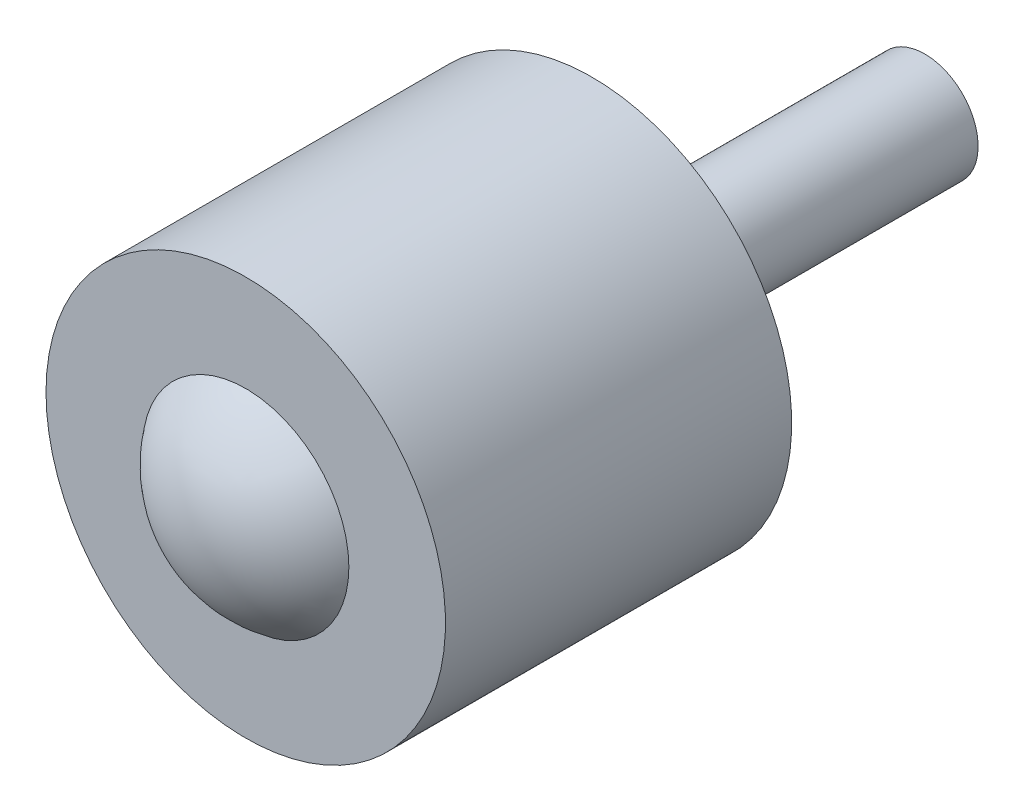
SolidWorks part; units mm, degrees
material "Cast Stainless Steel"
ref_plane "Front Plane" through (0, 0, 0) normal (0, 0, 1) x (1, 0, 0)
ref_plane "Top Plane" through (0, 0, 0) normal (0, 1, 0) x (1, 0, 0)
ref_plane "Right Plane" through (0, 0, 0) normal (1, 0, 0) x (0, 0, -1)
sketch "Sketch1" plane through (0, 0, 0) normal (0, 1, 0) x (1, 0, 0)
  line L0 (0, 9.5) -> (0, -9.5)
  arc A1 (0, -9.5) -> (0, 9.5) centre (0, 0) cw
  dimension "D1" = 19
  dimension "D2" = 9.5
revolve "Revolve6" add sketch "Sketch1" angle 360 about L0
sketch "Sketch2" plane through (0, 0, 0) normal (0, 1, 0) x (1, 0, 0)
  line L0 (0, 0) -> (-15, 0)
  line L1 (0, 0) -> (0, -9.5)
  line L2 (-15, 0) -> (-15, -5.5)
  line L3 (-15, -5.5) -> (0, -5.5)
  line L4 (0, 0) -> (0, 9.5)
  line L5 (-15, 0) -> (-15, 20.5)
  line L6 (-15, 20.5) -> (0, 20.5)
  line L7 (0, 20.5) -> (0, 9.5)
  arc A0 (-9.5, 0) -> (0, -9.5) centre (0, 0) ccw
  arc A1 (-9.5, 0) -> (0, 9.5) centre (0, 0) cw
  dimension "D1" = 9.5
  dimension "D2" = 4
  dimension "D3" = 26
  dimension "D4" = 15
revolve "Revolve7" add sketch "Sketch2" angle 360 about L7
ref_plane "Plane1" through (0, 0, 9.5) normal (0, 0, 1) x (1, 0, 0)
sketch "Sketch3" plane through (0, 0, -20.5) normal (0, 0, -1) x (-1, 0, 0)
  circle A0 centre (0, 0) radius 4
  dimension "D1" = 8
extrude "Boss-Extrude1" add sketch "Sketch3" along normal blind 25
